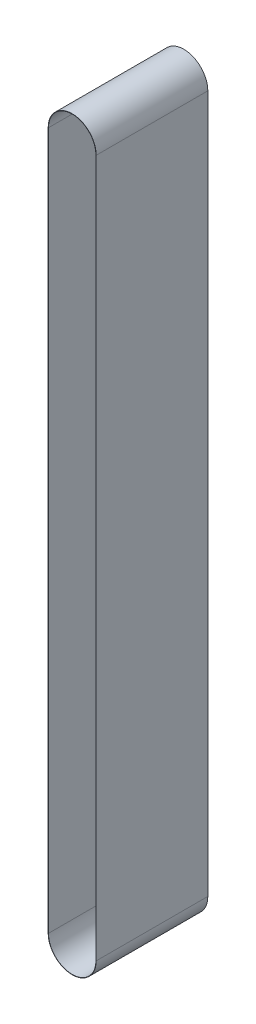
SolidWorks part; units mm, degrees
ref_plane "Front Plane" through (0, 0, 0) normal (0, 0, 1) x (1, 0, 0)
ref_plane "Top Plane" through (0, 0, 0) normal (0, 1, 0) x (1, 0, 0)
ref_plane "Right Plane" through (0, 0, 0) normal (1, 0, 0) x (0, 0, -1)
sketch "Sketch1" plane through (0, 0, 0) normal (0, 0, 1) x (1, 0, 0)
  line L0 (0, 250) -> (0, -250) construction
  line L1 (-17, -250) -> (-17, 250)
  line L2 (17, 250) -> (17, -250)
  line L3 (-17.2, -250) -> (-17.2, 250)
  line L4 (17.2, 250) -> (17.2, -250)
  circle A0 centre (0, 250) radius 17 construction
  circle A1 centre (0, -250) radius 17 construction
  arc A2 (-17, 250) -> (17, 250) centre (0, 250) cw
  arc A3 (-17, -250) -> (17, -250) centre (0, -250) ccw
  arc A4 (-17.2, 250) -> (17.2, 250) centre (0, 250) cw
  arc A5 (-17.2, -250) -> (17.2, -250) centre (0, -250) ccw
  point P4 (0, 0)
  dimension "D2" = 34
  dimension "D3" = 0.2
  dimension "D1" = 500
extrude "Boss-Extrude1" add sketch "Sketch1" along normal mid plane 80
sketch "Sketch3" plane through (0, 0, 0) normal (0, 0, 1) x (1, 0, 0)
  line L1 (-5, -262) -> (5, -262)
  line L2 (-5, -262) -> (-5, -272)
  line L3 (-5, -272) -> (5, -272)
  line L4 (5, -262) -> (5, -272)
  line L5 (-5, -262) -> (5, -272) construction
  line L6 (-5, -272) -> (5, -262) construction
  arc A0 (-17, -250) -> (17, -250) centre (0, -250) ccw construction
  point P0 (0, -267)
  dimension "D1" = 10
extrude "Cut-Extrude1" cut sketch "Sketch3" against normal mid plane 10 contours L4 L3 L2 L1
